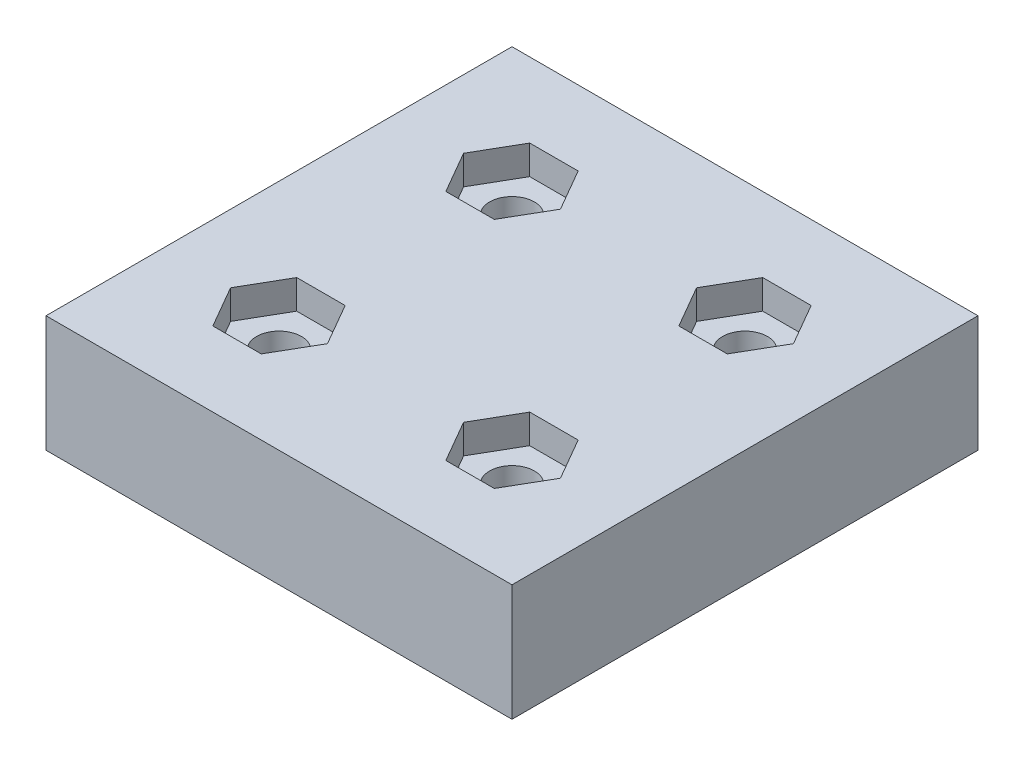
SolidWorks part; units mm, degrees
ref_plane "Front Plane" through (0, 0, 0) normal (0, 0, 1) x (1, 0, 0)
ref_plane "Top Plane" through (0, 0, 0) normal (0, 1, 0) x (1, 0, 0)
ref_plane "Right Plane" through (0, 0, 0) normal (1, 0, 0) x (0, 0, -1)
sketch "Sketch1" plane through (0, 0, 0) normal (0, 1, 0) x (1, 0, 0)
  line L1 (0, 0) -> (40, 0)
  line L2 (0, 0) -> (0, 40)
  line L3 (0, 40) -> (40, 40)
  line L4 (40, 0) -> (40, 40)
  circle A0 centre (10, 30) radius 1.925
  circle A1 centre (30, 30) radius 1.925
  circle A2 centre (30, 10) radius 1.925
  circle A3 centre (10, 10) radius 1.925
  dimension "D11" = 3.85
  dimension "D12" = 3.85
  dimension "D13" = 3.85
  dimension "D14" = 3.85
  dimension "D1" = 40
  dimension "D2" = 40
  dimension "D3" = 10
  dimension "D4" = 10
  dimension "D5" = 10
  dimension "D6" = 10
  dimension "D7" = 10
  dimension "D8" = 10
  dimension "D9" = 10
  dimension "D10" = 10
extrude "Boss-Extrude1" add sketch "Sketch1" along normal blind 10
sketch "Sketch2" plane through (0, 10, 0) normal (0, 1, 0) x (1, 0, 0)
  line L0 (10, 10) -> (30, 10) construction
  line L1 (30, 10) -> (30, 30) construction
  line L2 (30, 30) -> (10, 30) construction
  line L3 (10, 30) -> (10, 10) construction
  line L5 (14.1569, 10) -> (12.0785, 13.6)
  line L6 (12.0785, 13.6) -> (7.9215, 13.6)
  line L7 (7.9215, 13.6) -> (5.8431, 10)
  line L8 (5.8431, 10) -> (7.9215, 6.4)
  line L9 (7.9215, 6.4) -> (12.0785, 6.4)
  line L10 (12.0785, 6.4) -> (14.1569, 10)
  line L11 (25.8431, 10) -> (27.9215, 6.4)
  line L12 (27.9215, 6.4) -> (32.0785, 6.4)
  line L13 (32.0785, 6.4) -> (34.1569, 10)
  line L14 (34.1569, 10) -> (32.0785, 13.6)
  line L15 (32.0785, 13.6) -> (27.9215, 13.6)
  line L16 (27.9215, 13.6) -> (25.8431, 10)
  line L17 (25.8431, 30) -> (27.9215, 26.4)
  line L18 (27.9215, 26.4) -> (32.0785, 26.4)
  line L19 (32.0785, 26.4) -> (34.1569, 30)
  line L20 (34.1569, 30) -> (32.0785, 33.6)
  line L21 (32.0785, 33.6) -> (27.9215, 33.6)
  line L22 (27.9215, 33.6) -> (25.8431, 30)
  line L23 (14.1569, 30) -> (12.0785, 33.6)
  line L24 (12.0785, 33.6) -> (7.9215, 33.6)
  line L25 (7.9215, 33.6) -> (5.8431, 30)
  line L26 (5.8431, 30) -> (7.9215, 26.4)
  line L27 (7.9215, 26.4) -> (12.0785, 26.4)
  line L28 (12.0785, 26.4) -> (14.1569, 30)
  circle A0 centre (10, 10) radius 3.6 construction
  circle A1 centre (30, 10) radius 3.6 construction
  circle A2 centre (30, 30) radius 3.6 construction
  circle A3 centre (10, 30) radius 3.6 construction
  point P2 (0, 0)
  point P33 (0, 0)
  point P34 (0, 0)
  point P35 (0, 0)
  point P36 (0, 0)
  dimension "D1" = 7.2
  dimension "D2" = 7.2
  dimension "D3" = 7.2
  dimension "D4" = 7.2
extrude "Cut-Extrude1" cut sketch "Sketch2" against normal blind 2.5
equation "\"hSpacing\"=10"
equation "\"D3@Sketch1\"=\"hSpacing\""
equation "\"D5@Sketch1\"=\"hSpacing\""
equation "\"D6@Sketch1\"=\"hSpacing\""
equation "\"D4@Sketch1\"=\"hSpacing\""
equation "\"D7@Sketch1\"=\"hSpacing\""
equation "\"D8@Sketch1\"=\"hSpacing\""
equation "\"D9@Sketch1\"=\"hSpacing\""
equation "\"D10@Sketch1\"=\"hSpacing\""
equation "\"hDiam\"=3.85"
equation "\"D11@Sketch1\"=\"hDiam\""
equation "\"D12@Sketch1\"=\"hDiam\""
equation "\"D13@Sketch1\"=\"hDiam\""
equation "\"D14@Sketch1\"=\"hDiam\""
equation "\"nutFlat\"=7.2"
equation "\"D1@Sketch2\"=\"nutFlat\""
equation "\"D2@Sketch2\"=\"nutFlat\""
equation "\"D3@Sketch2\"=\"nutFlat\""
equation "\"D4@Sketch2\"=\"nutFlat\""
